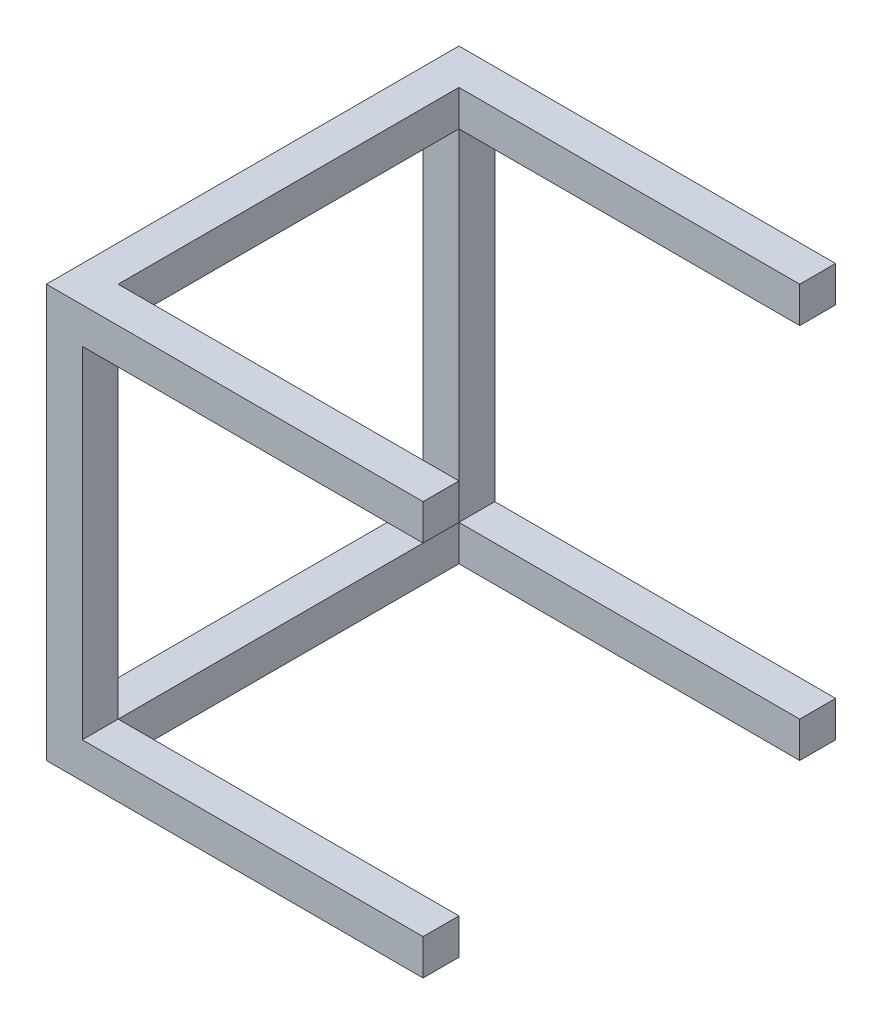
SolidWorks part; units mm, degrees
ref_plane "前视基准面" through (0, 0, 0) normal (0, 0, 1) x (1, 0, 0)
ref_plane "上视基准面" through (0, 0, 0) normal (0, 1, 0) x (1, 0, 0)
ref_plane "右视基准面" through (0, 0, 0) normal (1, 0, 0) x (0, 0, -1)
other "Configuration Table"
sketch "草图1" plane through (0, 0, 0) normal (1, 0, 0) x (0, 0, -1)
  line L21 (40, 65.5324) -> (420, 65.5324)
  line L22 (40, 65.5324) -> (40, 445.5324)
  line L23 (40, 445.5324) -> (420, 445.5324)
  line L24 (420, 65.5324) -> (420, 445.5324)
  line L33 (0, 25.5324) -> (460, 25.5324)
  line L34 (0, 25.5324) -> (0, 485.5324)
  line L35 (0, 485.5324) -> (460, 485.5324)
  line L36 (460, 25.5324) -> (460, 485.5324)
extrude "凸台-拉伸2" add sketch "草图1" along normal blind 40
sketch "草图2" plane through (40, 0, 0) normal (1, 0, 0) x (0, 0, -1)
  line L1 (0, 485.5324) -> (40, 485.5324)
  line L2 (0, 485.5324) -> (0, 445.5324)
  line L3 (0, 445.5324) -> (40, 445.5324)
  line L4 (40, 485.5324) -> (40, 445.5324)
  line L5 (460, 485.5324) -> (420, 485.5324)
  line L6 (460, 485.5324) -> (460, 445.5324)
  line L7 (460, 445.5324) -> (420, 445.5324)
  line L8 (420, 485.5324) -> (420, 445.5324)
  line L9 (460, 25.5324) -> (420, 25.5324)
  line L10 (460, 25.5324) -> (460, 65.5324)
  line L11 (460, 65.5324) -> (420, 65.5324)
  line L12 (420, 25.5324) -> (420, 65.5324)
  line L13 (0, 25.5324) -> (40, 25.5324)
  line L14 (0, 25.5324) -> (0, 65.5324)
  line L15 (0, 65.5324) -> (40, 65.5324)
  line L16 (40, 25.5324) -> (40, 65.5324)
extrude "凸台-拉伸3" add sketch "草图2" along normal blind 380
